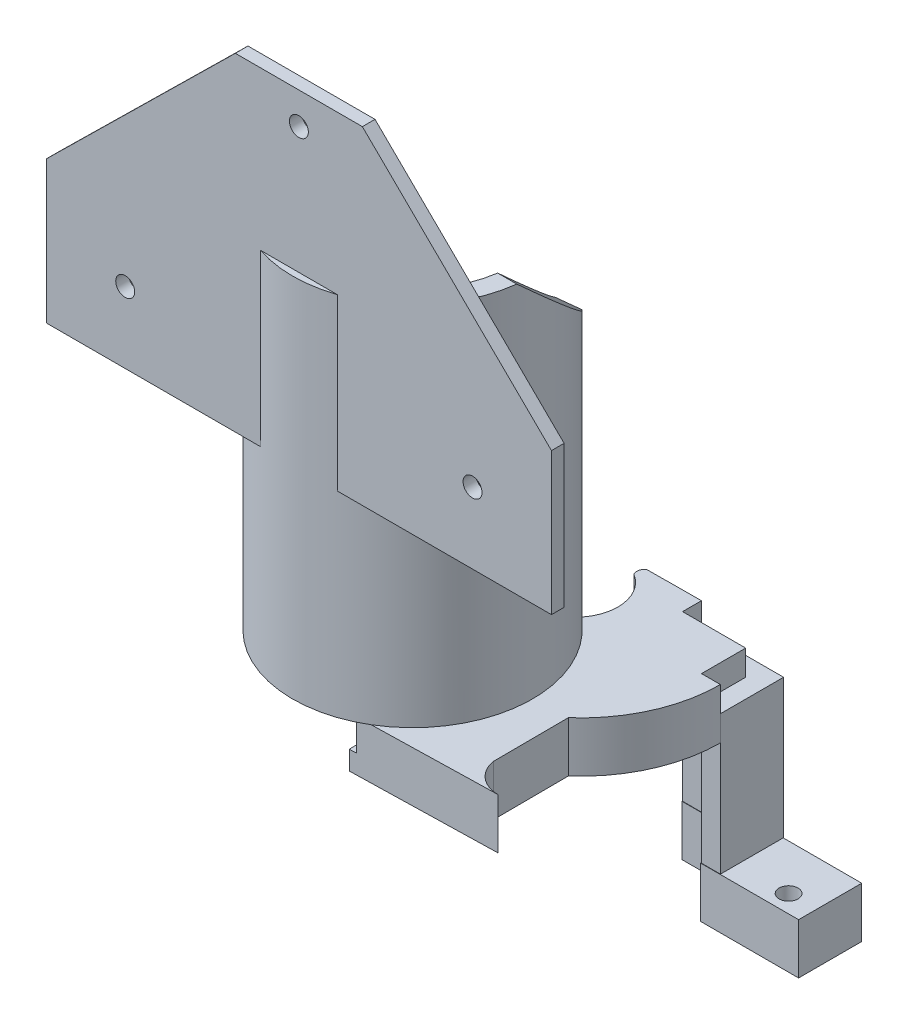
SolidWorks part; units mm, degrees
ref_plane "Front Plane" through (0, 0, 0) normal (0, 0, 1) x (1, 0, 0)
ref_plane "Top Plane" through (0, 0, 0) normal (0, 1, 0) x (1, 0, 0)
ref_plane "Right Plane" through (0, 0, 0) normal (1, 0, 0) x (0, 0, -1)
sketch "Sketch1" plane through (0, 0, 0) normal (0, 1, 0) x (1, 0, 0)
  circle A0 centre (0, 0) radius 19
  dimension "D1" = 38
extrude "Boss-Extrude1" add sketch "Sketch1" along normal blind 53 and the other way blind 5
sketch "Sketch2" plane through (0, 53, 0) normal (0, 1, 0) x (1, 0, 0)
  circle A0 centre (0, 0) radius 16
extrude "Cut-Extrude1" cut sketch "Sketch2" against normal blind 22
sketch "Sketch3" plane through (0, 53, 0) normal (0, 1, 0) x (1, 0, 0)
  line L1 (-12.5, 6) -> (12.5, 6)
  line L2 (-12.5, 6) -> (-12.5, 26)
  line L3 (-12.5, 26) -> (12.5, 26)
  line L4 (12.5, 6) -> (12.5, 26)
  line L5 (-12.5, 6) -> (12.5, 26) construction
  line L6 (-12.5, 26) -> (12.5, 6) construction
  circle A0 centre (0, 0) radius 16 construction
  point P0 (0, 16)
extrude "Cut-Extrude2" cut sketch "Sketch3" against normal blind 108
sketch "Sketch7" plane through (0, 0, 0) normal (1, 0, 0) x (0, 0, -1)
  line L0 (14.3091, 53) -> (14.3091, 38)
  line L1 (14.3091, -5) -> (14.3091, 53) construction
  line L2 (14.3091, 38) -> (-2.3455, 53)
  line L3 (14.3091, 53) -> (-19, 53) construction
  line L4 (-2.3455, 53) -> (14.3091, 53)
extrude "Cut-Extrude3" cut sketch "Sketch7" against normal blind 108 and the other way blind 108
ref_plane "Plane1" through (0, 0, 18) normal (0, 0, 1) x (1, 0, 0)
sketch "Sketch8" plane through (0, 0, 18) normal (0, 0, 1) x (1, 0, 0)
  line L1 (10.0571, 78.0232) -> (40, 48.5711)
  line L2 (40, 48.5711) -> (40, 26.0711)
  line L3 (40, 26.0711) -> (0, 26.0711)
  line L5 (0, -16.3611) -> (0, 16.3611) construction
  line L7 (-40, 26.0711) -> (0, 26.0711)
  line L8 (-40, 48.5711) -> (-40, 26.0711)
  line L9 (-10.0571, 78.0232) -> (-40, 48.5711)
  line L11 (-10.0571, 78.0232) -> (10.0571, 78.0232)
extrude "Boss-Extrude2" add sketch "Sketch8" against normal blind 2
sketch "Sketch10" plane through (0, 0, 16) normal (0, 0, -1) x (-1, 0, 0)
  line L0 (0, 53) -> (0, 73) construction
  line L1 (-19, 37.3211) -> (-27.5, 37.3211) construction
  line L2 (-19, 50.8876) -> (-19, -5) construction
  line L3 (19, 37.3211) -> (27.5, 37.3211) construction
  line L4 (19, -5) -> (19, 50.8876) construction
  circle A0 centre (-27.5, 37.3211) radius 1.5
  circle A1 centre (27.5, 37.3211) radius 1.5
  circle A2 centre (0, 73) radius 1.5
extrude "Cut-Extrude4" cut sketch "Sketch10" against normal blind 16
sketch "Sketch11" plane through (0, -5, 0) normal (0, -1, 0) x (1, 0, 0)
  line L0 (10.2759, -26.8054) -> (18.8909, -26.8634)
  line L1 (18.8909, -26.8634) -> (18.8909, -23.8634)
  line L2 (18.8909, -23.8634) -> (28.8909, -23.8634)
  line L3 (28.8909, -23.8634) -> (28.8909, -16.8634)
  line L4 (28.8909, -16.8634) -> (31.8909, -16.8634)
  line L5 (24.3909, -0.2751) -> (24.4524, 11.6188)
  line L6 (29.3909, 15.8366) -> (6.3756, 16.3864)
  line L7 (6.3756, 16.3864) -> (6.0124, 1.1829)
  line L8 (6.0124, 1.1829) -> (6.3909, -8.8634)
  line L9 (6.3909, -8.8634) -> (6.4802, -11.761)
  arc A0 (9.9319, -25.1296) -> (8.7246, -13.0297) centre (6.3756, -19.3742) ccw
  arc A1 (9.9319, -25.1296) -> (10.2759, -26.8054) centre (10.9418, -25.7955) ccw
  arc A2 (31.8909, -16.8634) -> (24.3909, -0.2751) centre (9.7961, -16.8634) ccw
  arc A3 (24.4524, 11.6188) -> (29.3909, 15.8366) centre (29.3908, 10.8366) cw
  arc A4 (6.4802, -11.761) -> (8.7246, -13.0297) centre (8.2368, -11.2731) ccw
extrude "Boss-Extrude3" add sketch "Sketch11" along normal blind 8
sketch "Sketch12" plane through (0, -13, 0) normal (0, -1, 0) x (1, 0, 0)
  line L10 (18.8909, -26.8634) -> (18.8909, -23.8634)
  line L11 (18.8909, -23.8634) -> (28.8909, -23.8634)
  line L12 (28.8909, -23.8634) -> (28.8909, -16.8634)
  line L13 (28.8909, -16.8634) -> (31.8909, -16.8634)
  line L14 (31.8909, -16.8634) -> (31.8909, -26.8634)
  line L15 (31.8909, -26.8634) -> (18.8909, -26.8634)
extrude "Boss-Extrude5" add sketch "Sketch12" along normal blind 18 and the other way blind 4 separate body
sketch "Sketch13" plane through (0, -31, 0) normal (0, -1, 0) x (1, 0, 0)
  line L0 (18.8227, -26.8076) -> (18.8227, -23.8076)
  line L1 (18.8227, -23.8076) -> (28.8227, -23.8076)
  line L2 (28.8227, -23.8076) -> (28.8227, -16.8076)
  line L3 (28.8227, -16.8076) -> (44.3227, -16.8076)
  line L4 (44.3227, -16.8076) -> (44.3227, -26.8076)
  line L5 (44.3227, -26.8076) -> (18.8227, -26.8076)
  circle A0 centre (39.936, -19.6077) radius 1.5002
extrude "Boss-Extrude6" add sketch "Sketch13" along normal blind 8
sketch "Sketch16" plane through (0, 31, 0) normal (0, 1, 0) x (1, 0, 0)
  circle A0 centre (0, 0) radius 18
extrude "Cut-Extrude5" cut sketch "Sketch16" against normal blind 41
